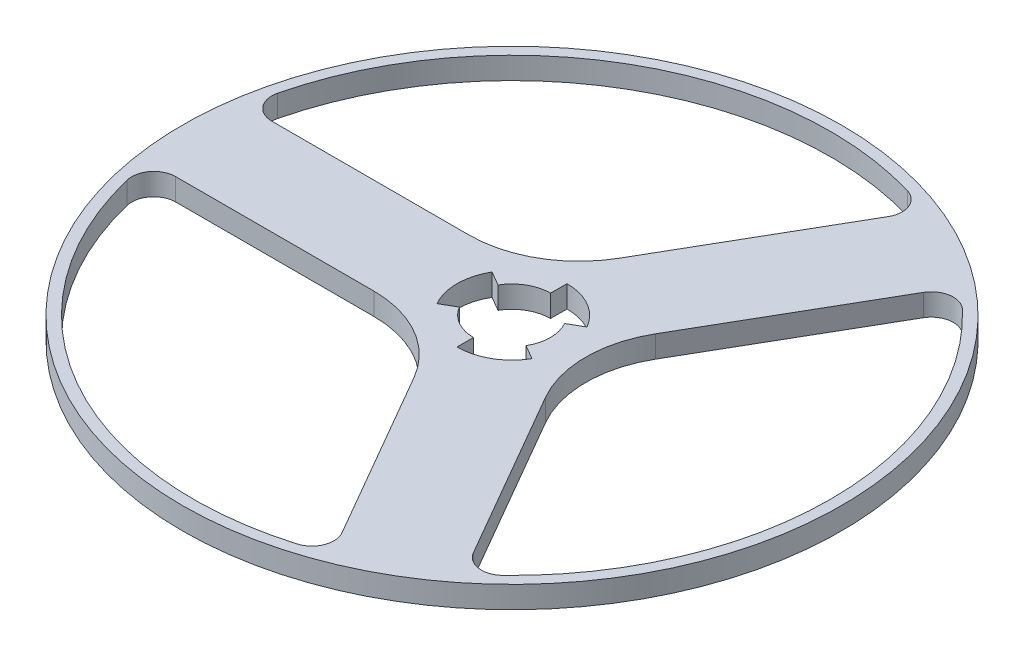
SolidWorks part; units mm, degrees
ref_plane "Front Plane" through (0, 0, 0) normal (0, 0, 1) x (1, 0, 0)
ref_plane "Top Plane" through (0, 0, 0) normal (0, 1, 0) x (1, 0, 0)
ref_plane "Right Plane" through (0, 0, 0) normal (1, 0, 0) x (0, 0, -1)
sketch "Sketch1" plane through (0, 0, 0) normal (0, 1, 0) x (1, 0, 0)
  line L0 (0, 15) -> (0, 0) construction
  line L1 (0, 0) -> (-12.9904, -7.5) construction
  line L2 (0, 0) -> (12.9904, -7.5) construction
  circle A0 centre (0, 0) radius 46.5
  circle A1 centre (0, 15) radius 6.5
  circle A2 centre (-12.9904, -7.5) radius 10
  circle A3 centre (12.9904, -7.5) radius 3.5
  circle A4 centre (0, 0) radius 3.5
  point P3 (0, 15)
  point P8 (12.9904, -7.5)
  point P9 (-12.9904, -7.5)
  point P10 (0, 0)
  dimension "D1" = 93
  dimension "D4" = 13
  dimension "D5" = 20
  dimension "D6" = 7
  dimension "D7" = 7
  dimension "D2" = 15
  dimension "D3" = 3
extrude "Boss-Extrude1" add sketch "Sketch1" along normal blind 2
sketch "Sketch2" plane through (0, 2, 0) normal (0, 1, 0) x (1, 0, 0)
  line L0 (0, 0) -> (12.9904, -7.5) construction
  line L1 (0, 0) -> (0, 46.5) construction
  line L2 (0, 0) -> (-12.9904, -7.5) construction
  line L3 (0, 0) -> (-40.2702, -23.25) construction
  line L4 (0, 0) -> (40.2702, -23.25) construction
  circle A0 centre (0, 0) radius 46.5 construction
  circle A1 centre (-12.9904, -7.5) radius 10 construction
  circle A2 centre (12.9904, -7.5) radius 3.5 construction
  circle A3 centre (0, 0) radius 25
  circle A4 centre (21.6506, -12.5) radius 3
  circle A5 centre (-21.6506, -12.5) radius 3
  circle A6 centre (0, 25) radius 3
  point P22 (0, 0)
  dimension "D1" = 50
  dimension "D2" = 6
  dimension "D3" = 3
ref_plane "Plane1" through (0, 0, 0) normal (-0.5, 0, -0.866) x (-0.866, 0, 0.5)
sketch "Sketch3" plane through (0, 2, 0) normal (0, 1, 0) x (1, 0, 0)
  circle A0 centre (0, 0) radius 3.5
  circle A1 centre (0, 0) radius 5
  dimension "D1" = 10
extrude "Boss-Extrude2" add sketch "Sketch3" along normal blind 100
sketch "Sketch4" plane through (0, 102, 0) normal (0, 1, 0) x (1, 0, 0)
  line L0 (-29, 0) -> (0, 0) construction
  line L6 (0, 0) -> (-2.5147, 4.3733) construction
  line L11 (-8.2882, 4.3733) -> (-28.6683, 4.3733)
  line L16 (-8.2093, -4.3733) -> (-28.6683, -4.3733)
  line L17 (7.9863, 5.0683) -> (18.1286, 22.6353)
  line L18 (0.372, 9.3733) -> (10.5551, 27.0109)
  line L19 (0.4509, -9.3733) -> (10.6194, -26.9857)
  line L20 (7.9863, -4.9317) -> (18.1825, -22.592)
  line L21 (0, 0) -> (-4.4122, 2.5577)
  line L22 (0, 0) -> (0.009, 5.1)
  line L23 (0, 0) -> (4.4212, 2.5422)
  line L24 (0, 0) -> (4.4122, -2.5577)
  line L25 (0, 0) -> (-0.009, -5.1)
  line L26 (0, 0) -> (-4.4212, -2.5422)
  line L27 (0, 0) -> (0, 54.3686) construction
  circle A0 centre (0, 0) radius 30
  circle A1 centre (0, 0) radius 29
  circle A2 centre (0, 0) radius 5.1
  circle A3 centre (0, 0) radius 3.5
  arc A4 (-8.2093, -4.3733) -> (0.4509, -9.3733) centre (-8.2093, -14.3733) cw
  circle A5 centre (0, 0) radius 5.1
  arc A6 (7.9863, -4.9317) -> (7.9863, 5.0683) centre (16.6465, 0.0683) cw
  arc A7 (-8.2882, 4.3733) -> (0.372, 9.3733) centre (-8.2882, 14.3733) ccw
  point P21 (0.0497, 0.0228)
  point P23 (0, 0)
  point P32 (0, 0)
  point P33 (5.0995, 0.0683)
  circle M18 centre (0, 0) radius 5
  circle M19 centre (0, 0) radius 3.5
  dimension "D1" = 60
  dimension "D2" = 58
  dimension "D11" = 10.2
  dimension "D12" = 10
  dimension "D4" = 3
  dimension "D7" = 8.7466
  dimension "D8" = 30
  dimension "D9" = 30
  dimension "D10" = 3
extrude "Boss-Extrude5" add sketch "Sketch4" along normal blind 2 separate body contours A7 L11 A1 L16 A4 L19 L20 A6 L17 L18 A5 | A0 A1 | L26 A2 L25 M18 | L22 A2 L21 M18 | L24 A2 L23 M18 | L21 A2 L26 M18 | L25 A2 L24 M18 | L23 A2 L22 M18 | L22 L21 M19 M18 | L26 L25 M19 M18 | L24 L23 M19 M18
fillet "Fillet2" radius 2 6 edges at (18.1825, 103, 22.592) (18.1286, 103, -22.6353) (10.5551, 103, -27.0109) (-28.6683, 103, -4.3733) (-28.6683, 103, 4.3733) (10.6194, 103, 26.9857)
sketch "Sketch5" plane through (0, 102, 0) normal (0, -1, 0) x (1, 0, 0)
  line L0 (0, 0) -> (-30, 0) construction
  line L1 (0, 0) -> (15, 25.9808) construction
  line L2 (0, 0) -> (15, -25.9808) construction
  line L6 (8.384, -16.5215) -> (4.884, -10.4593)
  line L7 (8.384, -16.5215) -> (10.116, -15.5215)
  line L8 (10.116, -15.5215) -> (6.616, -9.4593)
  line L9 (4.884, -10.4593) -> (6.616, -9.4593)
  line L10 (8.384, -16.5215) -> (6.616, -9.4593) construction
  line L11 (10.116, -15.5215) -> (4.884, -10.4593) construction
  circle A0 centre (0, 0) radius 15 construction
  circle A2 centre (-15, 0) radius 1
  circle A3 centre (7.5, 12.9904) radius 3.5
  point P17 (7.5, -12.9904)
  dimension "D1" = 30
  dimension "D2" = 2
  dimension "D3" = 7
  dimension "D4" = 2
  dimension "D5" = 7
extrude "Cut-Extrude1" cut sketch "Sketch5" against normal blind 1
sketch "Sketch6" plane through (0, 0, 0) normal (0, -1, 0) x (1, 0, 0)
  circle A0 centre (0, 0) radius 35
  circle A1 centre (0, 35) radius 2
  circle A2 centre (27.3641, 21.8221) radius 2
  circle A3 centre (34.1225, -7.7882) radius 2
  circle A4 centre (15.1859, -31.5339) radius 2
  circle A5 centre (-15.1859, -31.5339) radius 2
  circle A6 centre (-34.1225, -7.7882) radius 2
  circle A7 centre (-27.3641, 21.8221) radius 2
  point P20 (0, 0)
  dimension "D1" = 70
  dimension "D2" = 4
  dimension "D3" = 7
extrude "Cut-Extrude2" cut sketch "Sketch6" against normal up to next (2 mm away) contours A0 A4 | A0 A4 | A0 A3 | A0 A3 | A0 A2 | A0 A2 | A0 A1 | A0 A1 | A0 A7 | A0 A7 | A0 A6 | A0 A6 | A0 A5 | A0 A5
chamfer "Chamfer2" distance 0.8 angle 45 8 edges at (0, 0, 33) (-27.3641, 0, 19.8221) (-34.1225, 0, -9.7882) (-15.1859, 0, -33.5339) (27.3641, 0, 19.8221) (12.9904, 0, 11) (34.1225, 0, -9.7882) (15.1859, 0, -33.5339)
sketch "Sketch7" plane through (0, 102, 0) normal (0, -1, 0) x (1, 0, 0)
  circle A0 centre (0, 0) radius 61.0857
extrude "Cut-Extrude3" cut sketch "Sketch7" along normal through all
